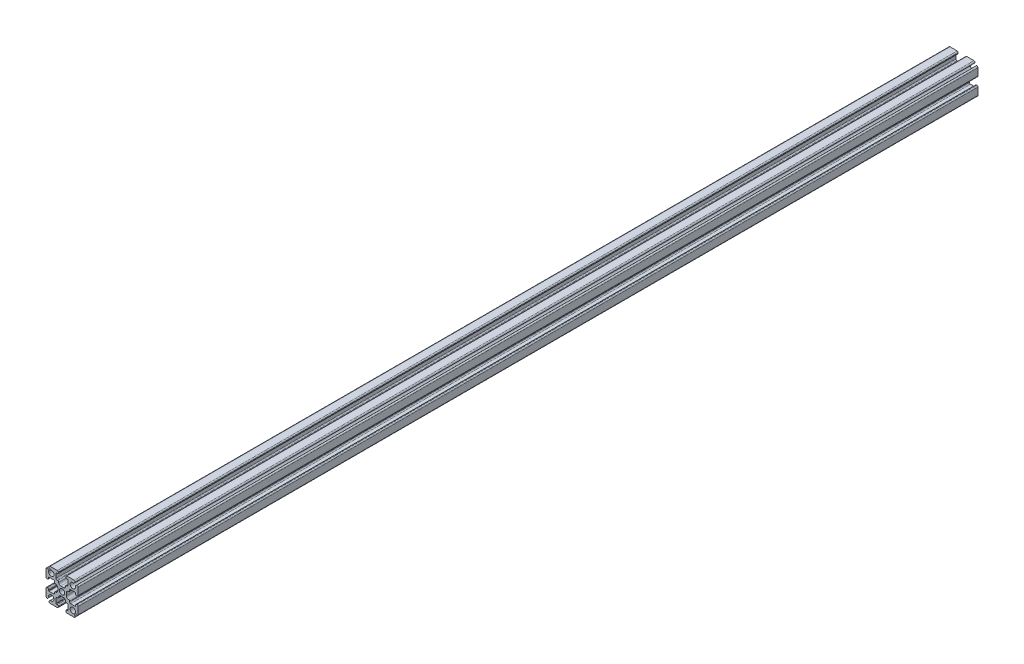
SolidWorks part; units mm, degrees
ref_plane "Front" through (0, 0, 0) normal (0, 0, 1) x (1, 0, 0)
ref_plane "Top" through (0, 0, 0) normal (0, 1, 0) x (1, 0, 0)
ref_plane "Right" through (0, 0, 0) normal (1, 0, 0) x (0, 0, -1)
sketch "Sketch1" plane through (0, 0, 0) normal (0, 0, 1) x (1, 0, 0)
  line L0 (6.6464, 5.9393) -> (6.1636, 5.4565)
  line L1 (5.4565, 6.1636) -> (5.9393, 6.6464)
  line L2 (5.5858, 7.5) -> (2.25, 7.5)
  line L3 (1.75, 7) -> (1.75, 6.8)
  line L4 (2.25, 6.3) -> (2.65, 6.3)
  line L5 (2.85, 6.1) -> (2.85, 4)
  line L6 (2.35, 3.5) -> (2.1, 3.5)
  line L7 (0.6, 2) -> (-0.6, 2)
  line L8 (-2.1, 3.5) -> (-2.35, 3.5)
  line L9 (-2.85, 4) -> (-2.85, 6.1)
  line L10 (-2.65, 6.3) -> (-2.25, 6.3)
  line L11 (-1.75, 6.8) -> (-1.75, 7)
  line L12 (-2.25, 7.5) -> (-5.5858, 7.5)
  line L13 (-5.9393, 6.6464) -> (-5.4565, 6.1636)
  line L14 (-6.1636, 5.4565) -> (-6.6464, 5.9393)
  line L15 (-7.5, 5.5858) -> (-7.5, 2.25)
  line L16 (-7, 1.75) -> (-6.8, 1.75)
  line L17 (-6.3, 2.25) -> (-6.3, 2.65)
  line L18 (-6.1, 2.85) -> (-4, 2.85)
  line L19 (-3.5, 2.35) -> (-3.5, 2.1)
  line L20 (-2, 0.6) -> (-2, -0.6)
  line L21 (-3.5, -2.1) -> (-3.5, -2.35)
  line L22 (-4, -2.85) -> (-6.1, -2.85)
  line L23 (-6.3, -2.65) -> (-6.3, -2.25)
  line L24 (-6.8, -1.75) -> (-7, -1.75)
  line L25 (-7.5, -2.25) -> (-7.5, -5.5858)
  line L26 (-6.6464, -5.9393) -> (-6.1636, -5.4565)
  line L27 (-5.4565, -6.1636) -> (-5.9393, -6.6464)
  line L28 (-5.5858, -7.5) -> (-2.25, -7.5)
  line L29 (-1.75, -7) -> (-1.75, -6.8)
  line L30 (-2.25, -6.3) -> (-2.65, -6.3)
  line L31 (-2.85, -6.1) -> (-2.85, -4)
  line L32 (-2.35, -3.5) -> (-2.1, -3.5)
  line L33 (-0.6, -2) -> (0.6, -2)
  line L34 (2.1, -3.5) -> (2.35, -3.5)
  line L35 (2.85, -4) -> (2.85, -6.1)
  line L36 (2.65, -6.3) -> (2.25, -6.3)
  line L37 (1.75, -6.8) -> (1.75, -7)
  line L38 (2.25, -7.5) -> (5.5858, -7.5)
  line L39 (5.9393, -6.6464) -> (5.4565, -6.1636)
  line L40 (6.1636, -5.4565) -> (6.6464, -5.9393)
  line L41 (7.5, -5.5858) -> (7.5, -2.25)
  line L42 (7, -1.75) -> (6.8, -1.75)
  line L43 (6.3, -2.25) -> (6.3, -2.65)
  line L44 (6.1, -2.85) -> (4, -2.85)
  line L45 (3.5, -2.35) -> (3.5, -2.1)
  line L46 (2, -0.6) -> (2, 0.6)
  line L47 (3.5, 2.1) -> (3.5, 2.35)
  line L48 (4, 2.85) -> (6.1, 2.85)
  line L49 (6.3, 2.65) -> (6.3, 2.25)
  line L50 (6.8, 1.75) -> (7, 1.75)
  line L51 (7.5, 2.25) -> (7.5, 5.5858)
  circle A0 centre (0, 0) radius 1.25
  arc A1 (6.1636, 5.4565) -> (5.4565, 6.1636) centre (5, 5) cw
  arc A2 (5.9393, 6.6464) -> (5.5858, 7.5) centre (5.5858, 7) ccw
  arc A3 (2.25, 7.5) -> (1.75, 7) centre (2.25, 7) ccw
  arc A4 (1.75, 6.8) -> (2.25, 6.3) centre (2.25, 6.8) ccw
  arc A5 (2.65, 6.3) -> (2.85, 6.1) centre (2.65, 6.1) cw
  arc A6 (2.85, 4) -> (2.35, 3.5) centre (2.35, 4) cw
  arc A7 (2.1, 3.5) -> (1.6, 3) centre (2.1, 3) ccw
  arc A8 (1.6, 3) -> (0.6, 2) centre (0.6, 3) cw
  arc A9 (-0.6, 2) -> (-1.6, 3) centre (-0.6, 3) cw
  arc A10 (-1.6, 3) -> (-2.1, 3.5) centre (-2.1, 3) ccw
  arc A11 (-2.35, 3.5) -> (-2.85, 4) centre (-2.35, 4) cw
  arc A12 (-2.85, 6.1) -> (-2.65, 6.3) centre (-2.65, 6.1) cw
  arc A13 (-2.25, 6.3) -> (-1.75, 6.8) centre (-2.25, 6.8) ccw
  arc A14 (-1.75, 7) -> (-2.25, 7.5) centre (-2.25, 7) ccw
  arc A15 (-5.5858, 7.5) -> (-5.9393, 6.6464) centre (-5.5858, 7) ccw
  arc A16 (-5.4565, 6.1636) -> (-6.1636, 5.4565) centre (-5, 5) cw
  arc A17 (-6.6464, 5.9393) -> (-7.5, 5.5858) centre (-7, 5.5858) ccw
  arc A18 (-7.5, 2.25) -> (-7, 1.75) centre (-7, 2.25) ccw
  arc A19 (-6.8, 1.75) -> (-6.3, 2.25) centre (-6.8, 2.25) ccw
  arc A20 (-6.3, 2.65) -> (-6.1, 2.85) centre (-6.1, 2.65) cw
  arc A21 (-4, 2.85) -> (-3.5, 2.35) centre (-4, 2.35) cw
  arc A22 (-3.5, 2.1) -> (-3, 1.6) centre (-3, 2.1) ccw
  arc A23 (-3, 1.6) -> (-2, 0.6) centre (-3, 0.6) cw
  arc A24 (-2, -0.6) -> (-3, -1.6) centre (-3, -0.6) cw
  arc A25 (-3, -1.6) -> (-3.5, -2.1) centre (-3, -2.1) ccw
  arc A26 (-3.5, -2.35) -> (-4, -2.85) centre (-4, -2.35) cw
  arc A27 (-6.1, -2.85) -> (-6.3, -2.65) centre (-6.1, -2.65) cw
  arc A28 (-6.3, -2.25) -> (-6.8, -1.75) centre (-6.8, -2.25) ccw
  arc A29 (-7, -1.75) -> (-7.5, -2.25) centre (-7, -2.25) ccw
  arc A30 (-7.5, -5.5858) -> (-6.6464, -5.9393) centre (-7, -5.5858) ccw
  arc A31 (-6.1636, -5.4565) -> (-5.4565, -6.1636) centre (-5, -5) cw
  arc A32 (-5.9393, -6.6464) -> (-5.5858, -7.5) centre (-5.5858, -7) ccw
  arc A33 (-2.25, -7.5) -> (-1.75, -7) centre (-2.25, -7) ccw
  arc A34 (-1.75, -6.8) -> (-2.25, -6.3) centre (-2.25, -6.8) ccw
  arc A35 (-2.65, -6.3) -> (-2.85, -6.1) centre (-2.65, -6.1) cw
  arc A36 (-2.85, -4) -> (-2.35, -3.5) centre (-2.35, -4) cw
  arc A37 (-2.1, -3.5) -> (-1.6, -3) centre (-2.1, -3) ccw
  arc A38 (-1.6, -3) -> (-0.6, -2) centre (-0.6, -3) cw
  arc A39 (0.6, -2) -> (1.6, -3) centre (0.6, -3) cw
  arc A40 (1.6, -3) -> (2.1, -3.5) centre (2.1, -3) ccw
  arc A41 (2.35, -3.5) -> (2.85, -4) centre (2.35, -4) cw
  arc A42 (2.85, -6.1) -> (2.65, -6.3) centre (2.65, -6.1) cw
  arc A43 (2.25, -6.3) -> (1.75, -6.8) centre (2.25, -6.8) ccw
  arc A44 (1.75, -7) -> (2.25, -7.5) centre (2.25, -7) ccw
  arc A45 (5.5858, -7.5) -> (5.9393, -6.6464) centre (5.5858, -7) ccw
  arc A46 (5.4565, -6.1636) -> (6.1636, -5.4565) centre (5, -5) cw
  arc A47 (6.6464, -5.9393) -> (7.5, -5.5858) centre (7, -5.5858) ccw
  arc A48 (7.5, -2.25) -> (7, -1.75) centre (7, -2.25) ccw
  arc A49 (6.8, -1.75) -> (6.3, -2.25) centre (6.8, -2.25) ccw
  arc A50 (6.3, -2.65) -> (6.1, -2.85) centre (6.1, -2.65) cw
  arc A51 (4, -2.85) -> (3.5, -2.35) centre (4, -2.35) cw
  arc A52 (3.5, -2.1) -> (3, -1.6) centre (3, -2.1) ccw
  arc A53 (3, -1.6) -> (2, -0.6) centre (3, -0.6) cw
  arc A54 (2, 0.6) -> (3, 1.6) centre (3, 0.6) cw
  arc A55 (3, 1.6) -> (3.5, 2.1) centre (3, 2.1) ccw
  arc A56 (3.5, 2.35) -> (4, 2.85) centre (4, 2.35) cw
  arc A57 (6.1, 2.85) -> (6.3, 2.65) centre (6.1, 2.65) cw
  arc A58 (6.3, 2.25) -> (6.8, 1.75) centre (6.8, 2.25) ccw
  arc A59 (7, 1.75) -> (7.5, 2.25) centre (7, 2.25) ccw
  arc A60 (7.5, 5.5858) -> (6.6464, 5.9393) centre (7, 5.5858) ccw
extrude "Boss-Extrude1" add sketch "Sketch1" along normal blind 420
